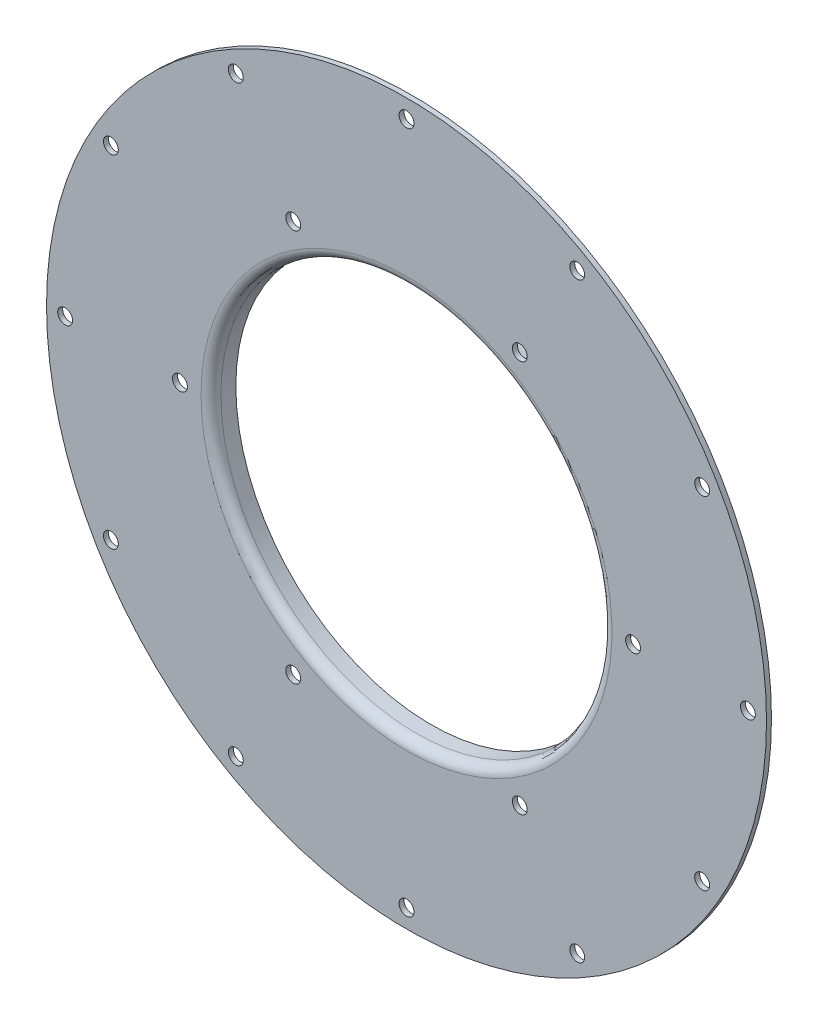
SolidWorks part; units mm, degrees
material "ASTM A36 Steel"
ref_plane "Front Plane" through (0, 0, 0) normal (0, 0, 1) x (1, 0, 0)
ref_plane "Top Plane" through (0, 0, 0) normal (0, 1, 0) x (1, 0, 0)
ref_plane "Right Plane" through (0, 0, 0) normal (1, 0, 0) x (0, 0, -1)
sketch "Sketch1" plane through (0, 0, 0) normal (0, 1, 0) x (1, 0, 0)
  line L0 (-161.5, 8) -> (-161.5, 20)
  line L1 (0, 0) -> (0, -23.2702)
  line L2 (-157.5, 8) -> (-157.5, 20)
  line L3 (-165.5, 0) -> (-290, 0)
  line L4 (-165.5, 4) -> (-290, 4)
  line L5 (-157.5, 20) -> (-161.5, 20)
  line L6 (-290, 4) -> (-290, 0)
  arc A0 (-157.5, 8) -> (-165.5, 0) centre (-165.5, 8) cw
  arc A1 (-161.5, 8) -> (-165.5, 4) centre (-165.5, 8) cw
  point P8 (-157.5, 0)
  dimension "D3" = 8
  dimension "D1" = 4
  dimension "D2" = 20
revolve "Revolve1" add sketch "Sketch1" angle 360 about L1
sketch "Sketch2" plane through (0, 0, 0) normal (0, 0, 1) x (1, 0, 0)
  circle A1 centre (182.5, 0) radius 6
  dimension "D2" = 12
extrude "Cut-Extrude1" cut sketch "Sketch2" against normal blind 10
pattern_circular "CirPattern1" count 6 over 360 about axis through (0, 0, 0) along (0, 0, 1) of "Cut-Extrude1"
sketch "Sketch3" plane through (0, 0, 0) normal (0, 0, 1) x (1, 0, 0)
  circle A1 centre (275, 0) radius 6
  dimension "D2" = 12
extrude "Cut-Extrude2" cut sketch "Sketch3" against normal blind 10
pattern_circular "CirPattern2" count 12 over 360 about axis through (0, 0, 0) along (0, 0, 1) of "Cut-Extrude2"
